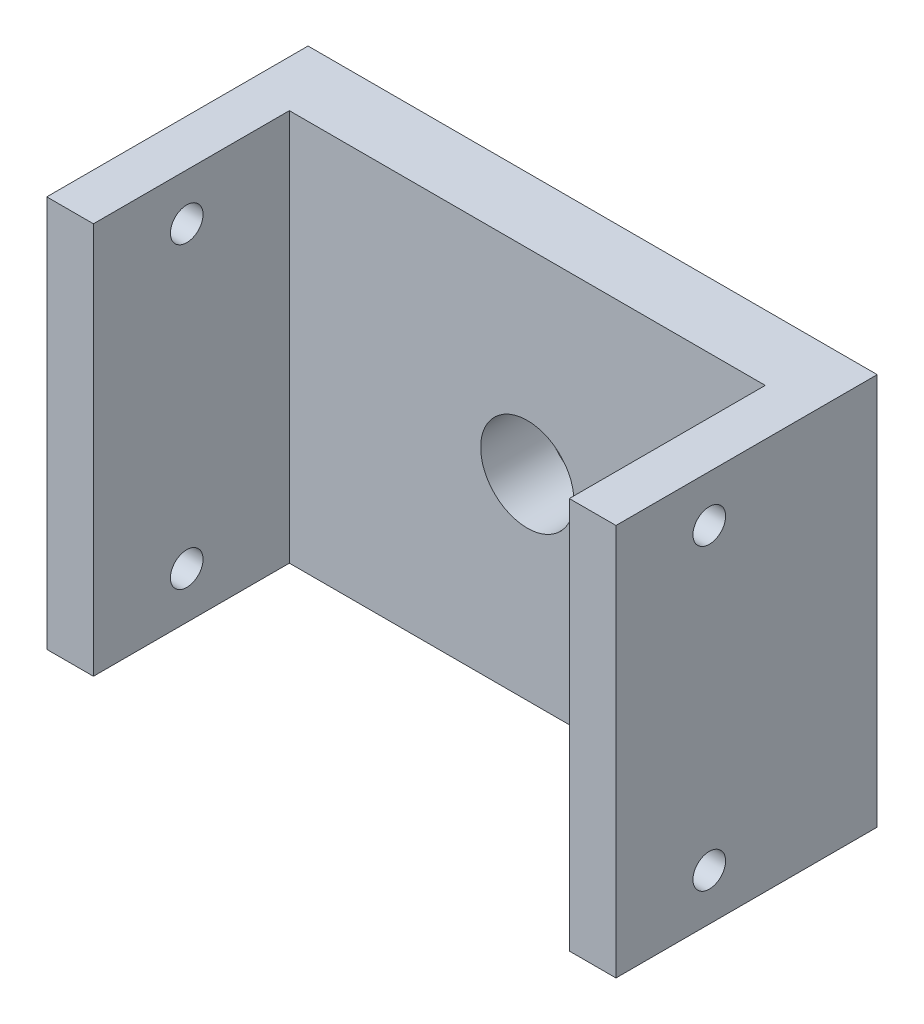
SolidWorks part; units mm, degrees
ref_plane "Front Plane" through (0, 0, 0) normal (0, 0, 1) x (1, 0, 0)
ref_plane "Top Plane" through (0, 0, 0) normal (0, 1, 0) x (1, 0, 0)
ref_plane "Right Plane" through (0, 0, 0) normal (1, 0, 0) x (0, 0, -1)
sketch "Sketch1" plane through (0, 0, 0) normal (0, 0, 1) x (1, 0, 0)
  line L1 (-30.5, 21) -> (30.5, 21)
  line L2 (-30.5, 21) -> (-30.5, -21)
  line L3 (-30.5, -21) -> (30.5, -21)
  line L4 (30.5, 21) -> (30.5, -21)
  line L5 (-30.5, 21) -> (30.5, -21) construction
  line L6 (-30.5, -21) -> (30.5, 21) construction
  circle A0 centre (0, 0) radius 5
  point P0 (0, 0)
  dimension "D3" = 10
  dimension "D1" = 42
  dimension "D2" = 61
extrude "Boss-Extrude1" add sketch "Sketch1" along normal blind 7
sketch "Sketch2" plane through (0, 0, 7) normal (0, 0, 1) x (1, 0, 0)
  line L0 (-30.5, -21) -> (30.5, -21) construction
  line L1 (-30.5, 21) -> (-25.5, 21)
  line L2 (-30.5, 21) -> (-30.5, -21)
  line L3 (-30.5, -21) -> (-25.5, -21)
  line L4 (-25.5, 21) -> (-25.5, -21)
  line L5 (0, 10.614) -> (0, 0) construction
  line L6 (25.5, 21) -> (25.5, -21)
  line L7 (30.5, -21) -> (25.5, -21)
  line L8 (30.5, 21) -> (30.5, -21)
  line L9 (30.5, 21) -> (25.5, 21)
  dimension "D1" = 5
extrude "Boss-Extrude2" add sketch "Sketch2" along normal blind 21
sketch "Sketch3" plane through (30.5, 0, 0) normal (1, 0, 0) x (0, 0, -1)
  line L0 (-28, -21) -> (-28, 21) construction
  line L1 (-28, 21) -> (0, 21) construction
  line L2 (-4.8012, 0) -> (-16.4054, 0) construction
  circle A0 centre (-18, 16) radius 1.75
  circle A1 centre (-18, -16) radius 1.75
  dimension "D1" = 10
  dimension "D3" = 3.5
  dimension "D2" = 5
extrude "Cut-Extrude1" cut sketch "Sketch3" against normal through all
